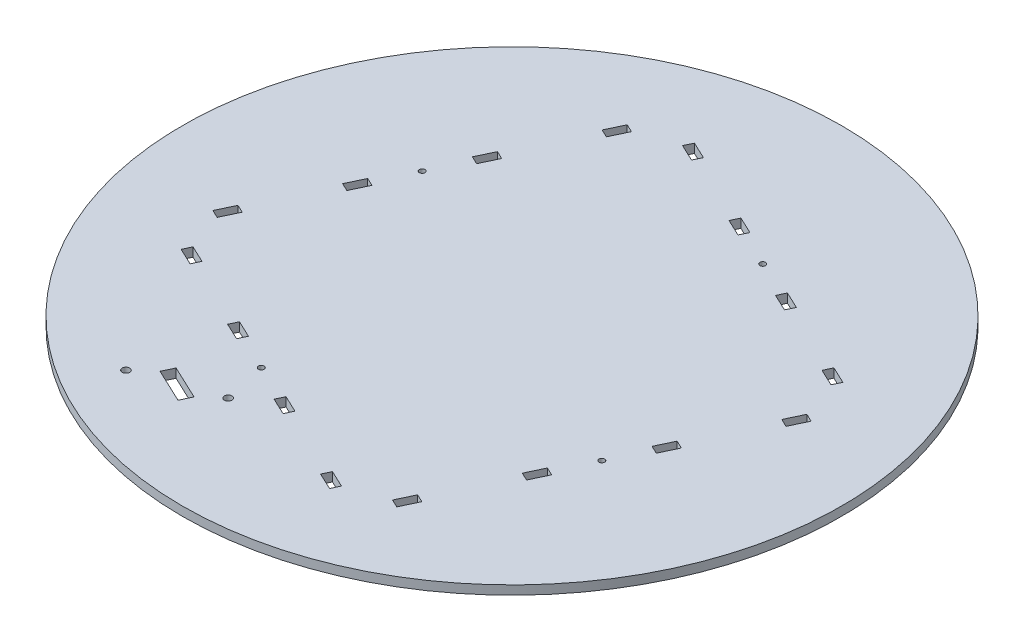
SolidWorks part; units mm, degrees
material "Oak"
ref_plane "Front Plane" through (0, 0, 0) normal (0, 0, 1) x (1, 0, 0)
ref_plane "Top Plane" through (0, 0, 0) normal (0, 1, 0) x (1, 0, 0)
ref_plane "Right Plane" through (0, 0, 0) normal (1, 0, 0) x (0, 0, -1)
sketch "Sketch1" plane through (0, 0, 0) normal (0, 1, 0) x (1, 0, 0)
  circle A0 centre (0, 0) radius 175
  dimension "D1" = 350
extrude "Boss-Extrude1" add sketch "Sketch1" along normal blind 4.75
sketch "Sketch2" plane through (0, 4.75, 0) normal (0, 1, 0) x (1, 0, 0)
  line L0 (33.006, -123.5643) -> (23.9642, -119.2927) construction
  line L1 (23.9642, -119.2927) -> (21.9352, -123.5875) construction
  line L2 (21.9352, -123.5875) -> (30.977, -127.8591) construction
  line L3 (30.977, -127.8591) -> (33.006, -123.5643) construction
  line L4 (-13.7851, -101.4587) -> (-22.8269, -97.1871) construction
  line L5 (-22.8269, -97.1871) -> (-24.8559, -101.482) construction
  line L6 (-24.8559, -101.482) -> (-15.8141, -105.7536) construction
  line L7 (-15.8141, -105.7536) -> (-13.7851, -101.4587) construction
  line L8 (-107.3673, -57.2476) -> (-116.4091, -52.976) construction
  line L9 (-116.4091, -52.976) -> (-118.4381, -57.2709) construction
  line L10 (-118.4381, -57.2709) -> (-109.3963, -61.5425) construction
  line L11 (-109.3963, -61.5425) -> (-107.3673, -57.2476) construction
  line L12 (-101.4587, 13.7851) -> (-97.1871, 22.8269) construction
  line L13 (-97.1871, 22.8269) -> (-101.482, 24.8559) construction
  line L14 (-101.482, 24.8559) -> (-105.7536, 15.8141) construction
  line L15 (-105.7536, 15.8141) -> (-101.4587, 13.7851) construction
  line L16 (-123.5643, -33.006) -> (-119.2927, -23.9642) construction
  line L17 (-119.2927, -23.9642) -> (-123.5875, -21.9352) construction
  line L18 (-123.5875, -21.9352) -> (-127.8591, -30.977) construction
  line L19 (-127.8591, -30.977) -> (-123.5643, -33.006) construction
  line L20 (33.006, -123.5643) -> (23.9642, -119.2927)
  line L21 (23.9642, -119.2927) -> (21.9352, -123.5875)
  line L22 (21.9352, -123.5875) -> (30.977, -127.8591)
  line L23 (30.977, -127.8591) -> (33.006, -123.5643)
  line L24 (-13.7851, -101.4587) -> (-22.8269, -97.1871)
  line L25 (-22.8269, -97.1871) -> (-24.8559, -101.482)
  line L26 (-24.8559, -101.482) -> (-15.8141, -105.7536)
  line L27 (-15.8141, -105.7536) -> (-13.7851, -101.4587)
  line L28 (-107.3673, -57.2476) -> (-116.4091, -52.976)
  line L29 (-116.4091, -52.976) -> (-118.4381, -57.2709)
  line L30 (-118.4381, -57.2709) -> (-109.3963, -61.5425)
  line L31 (-109.3963, -61.5425) -> (-107.3673, -57.2476)
  line L32 (-101.4587, 13.7851) -> (-97.1871, 22.8269)
  line L33 (-97.1871, 22.8269) -> (-101.482, 24.8559)
  line L34 (-101.482, 24.8559) -> (-105.7536, 15.8141)
  line L35 (-105.7536, 15.8141) -> (-101.4587, 13.7851)
  line L36 (-123.5643, -33.006) -> (-119.2927, -23.9642)
  line L37 (-119.2927, -23.9642) -> (-123.5875, -21.9352)
  line L38 (-123.5875, -21.9352) -> (-127.8591, -30.977)
  line L39 (-127.8591, -30.977) -> (-123.5643, -33.006)
  line L40 (107.3673, 57.2476) -> (116.4091, 52.976) construction
  line L41 (116.4091, 52.976) -> (118.4381, 57.2709) construction
  line L42 (118.4381, 57.2709) -> (109.3963, 61.5425) construction
  line L43 (109.3963, 61.5425) -> (107.3673, 57.2476) construction
  line L44 (-57.2476, 107.3673) -> (-52.976, 116.4091) construction
  line L45 (-52.976, 116.4091) -> (-57.2709, 118.4381) construction
  line L46 (-57.2709, 118.4381) -> (-61.5425, 109.3963) construction
  line L47 (-61.5425, 109.3963) -> (-57.2476, 107.3673) construction
  line L48 (60.5762, 79.3532) -> (69.618, 75.0816) construction
  line L49 (69.618, 75.0816) -> (71.647, 79.3764) construction
  line L50 (71.647, 79.3764) -> (62.6052, 83.648) construction
  line L51 (62.6052, 83.648) -> (60.5762, 79.3532) construction
  line L52 (13.7851, 101.4587) -> (22.8269, 97.1871) construction
  line L53 (22.8269, 97.1871) -> (24.8559, 101.482) construction
  line L54 (24.8559, 101.482) -> (15.8141, 105.7536) construction
  line L55 (15.8141, 105.7536) -> (13.7851, 101.4587) construction
  line L56 (-33.006, 123.5643) -> (-23.9642, 119.2927) construction
  line L57 (-23.9642, 119.2927) -> (-21.9352, 123.5875) construction
  line L58 (-21.9352, 123.5875) -> (-30.977, 127.8591) construction
  line L59 (-30.977, 127.8591) -> (-33.006, 123.5643) construction
  line L60 (-79.3532, 60.5762) -> (-75.0816, 69.618) construction
  line L61 (-75.0816, 69.618) -> (-79.3764, 71.647) construction
  line L62 (-79.3764, 71.647) -> (-83.648, 62.6052) construction
  line L63 (-83.648, 62.6052) -> (-79.3532, 60.5762) construction
  line L64 (-60.5762, -79.3532) -> (-69.618, -75.0816) construction
  line L65 (-69.618, -75.0816) -> (-71.647, -79.3764) construction
  line L66 (-71.647, -79.3764) -> (-62.6052, -83.648) construction
  line L67 (-62.6052, -83.648) -> (-60.5762, -79.3532) construction
  line L68 (123.5643, 33.006) -> (119.2927, 23.9642) construction
  line L69 (119.2927, 23.9642) -> (123.5875, 21.9352) construction
  line L70 (123.5875, 21.9352) -> (127.8591, 30.977) construction
  line L71 (127.8591, 30.977) -> (123.5643, 33.006) construction
  line L72 (101.4587, -13.7851) -> (97.1871, -22.8269) construction
  line L73 (97.1871, -22.8269) -> (101.482, -24.8559) construction
  line L74 (101.482, -24.8559) -> (105.7536, -15.8141) construction
  line L75 (105.7536, -15.8141) -> (101.4587, -13.7851) construction
  line L76 (79.3532, -60.5762) -> (75.0816, -69.618) construction
  line L77 (75.0816, -69.618) -> (79.3764, -71.647) construction
  line L78 (79.3764, -71.647) -> (83.648, -62.6052) construction
  line L79 (83.648, -62.6052) -> (79.3532, -60.5762) construction
  line L80 (57.2476, -107.3673) -> (52.976, -116.4091) construction
  line L81 (52.976, -116.4091) -> (57.2709, -118.4381) construction
  line L82 (57.2709, -118.4381) -> (61.5425, -109.3963) construction
  line L83 (61.5425, -109.3963) -> (57.2476, -107.3673) construction
  line L84 (107.3673, 57.2476) -> (116.4091, 52.976)
  line L85 (116.4091, 52.976) -> (118.4381, 57.2709)
  line L86 (118.4381, 57.2709) -> (109.3963, 61.5425)
  line L87 (109.3963, 61.5425) -> (107.3673, 57.2476)
  line L88 (-57.2476, 107.3673) -> (-52.976, 116.4091)
  line L89 (-52.976, 116.4091) -> (-57.2709, 118.4381)
  line L90 (-57.2709, 118.4381) -> (-61.5425, 109.3963)
  line L91 (-61.5425, 109.3963) -> (-57.2476, 107.3673)
  line L92 (60.5762, 79.3532) -> (69.618, 75.0816)
  line L93 (69.618, 75.0816) -> (71.647, 79.3764)
  line L94 (71.647, 79.3764) -> (62.6052, 83.648)
  line L95 (62.6052, 83.648) -> (60.5762, 79.3532)
  line L96 (13.7851, 101.4587) -> (22.8269, 97.1871)
  line L97 (22.8269, 97.1871) -> (24.8559, 101.482)
  line L98 (24.8559, 101.482) -> (15.8141, 105.7536)
  line L99 (15.8141, 105.7536) -> (13.7851, 101.4587)
  line L100 (-33.006, 123.5643) -> (-23.9642, 119.2927)
  line L101 (-23.9642, 119.2927) -> (-21.9352, 123.5875)
  line L102 (-21.9352, 123.5875) -> (-30.977, 127.8591)
  line L103 (-30.977, 127.8591) -> (-33.006, 123.5643)
  line L104 (-79.3532, 60.5762) -> (-75.0816, 69.618)
  line L105 (-75.0816, 69.618) -> (-79.3764, 71.647)
  line L106 (-79.3764, 71.647) -> (-83.648, 62.6052)
  line L107 (-83.648, 62.6052) -> (-79.3532, 60.5762)
  line L108 (-60.5762, -79.3532) -> (-69.618, -75.0816)
  line L109 (-69.618, -75.0816) -> (-71.647, -79.3764)
  line L110 (-71.647, -79.3764) -> (-62.6052, -83.648)
  line L111 (-62.6052, -83.648) -> (-60.5762, -79.3532)
  line L112 (123.5643, 33.006) -> (119.2927, 23.9642)
  line L113 (119.2927, 23.9642) -> (123.5875, 21.9352)
  line L114 (123.5875, 21.9352) -> (127.8591, 30.977)
  line L115 (127.8591, 30.977) -> (123.5643, 33.006)
  line L116 (101.4587, -13.7851) -> (97.1871, -22.8269)
  line L117 (97.1871, -22.8269) -> (101.482, -24.8559)
  line L118 (101.482, -24.8559) -> (105.7536, -15.8141)
  line L119 (105.7536, -15.8141) -> (101.4587, -13.7851)
  line L120 (79.3532, -60.5762) -> (75.0816, -69.618)
  line L121 (75.0816, -69.618) -> (79.3764, -71.647)
  line L122 (79.3764, -71.647) -> (83.648, -62.6052)
  line L123 (83.648, -62.6052) -> (79.3532, -60.5762)
  line L124 (57.2476, -107.3673) -> (52.976, -116.4091)
  line L125 (52.976, -116.4091) -> (57.2709, -118.4381)
  line L126 (57.2709, -118.4381) -> (61.5425, -109.3963)
  line L127 (61.5425, -109.3963) -> (57.2476, -107.3673)
extrude "Cut-Extrude1" cut sketch "Sketch2" against normal blind 4.75
sketch "Sketch3" plane through (0, 4.75, 0) normal (0, 1, 0) x (1, 0, 0)
  line L0 (12.4764, 52.4112) -> (39.3092, 38.9948)
  line L1 (12.4764, 52.4112) -> (41.5453, 110.549)
  line L2 (39.3092, 38.9948) -> (68.3781, 97.1326)
  line L3 (41.5453, 110.549) -> (68.3781, 97.1326)
  line L4 (23.6567, 97.1326) -> (68.3781, 130.6736)
  line L5 (68.3781, 130.6736) -> (68.3781, 74.7719)
  line L6 (68.3781, 74.7719) -> (23.6567, 97.1326)
  point P8 (25.8928, 45.703)
  dimension "D1" = 30
  dimension "D2" = 45
  dimension "D3" = 65
  dimension "D4" = 50
sketch "Sketch4" plane through (0, 4.75, 0) normal (0, 1, 0) x (1, 0, 0)
  line L0 (-47.129, -121.7057) -> (-65.2125, -113.1625) construction
  line L1 (-65.2125, -113.1625) -> (-67.9463, -118.9492) construction
  line L2 (-49.8628, -127.4924) -> (-47.129, -121.7057) construction
  line L3 (-67.9463, -118.9492) -> (-49.8628, -127.4924) construction
  line L4 (-47.129, -121.7057) -> (-65.2125, -113.1625)
  line L5 (-65.2125, -113.1625) -> (-67.9463, -118.9492)
  line L6 (-49.8628, -127.4924) -> (-47.129, -121.7057)
  line L7 (-67.9463, -118.9492) -> (-49.8628, -127.4924)
  circle A0 centre (-77.5077, -127.4827) radius 2 construction
  circle A1 centre (-37.5676, -113.1722) radius 2 construction
  circle A2 centre (-77.5077, -127.4827) radius 2
  circle A3 centre (-37.5676, -113.1722) radius 2
extrude "Cut-Extrude2" cut sketch "Sketch4" against normal through all
sketch "Sketch5" plane through (0, 4.75, 0) normal (0, 1, 0) x (1, 0, 0)
  line L0 (44.0723, 89.7768) -> (41.3598, 91.0583) construction
  line L1 (43.0578, 87.6294) -> (45.0868, 91.9243) construction
  line L4 (40.3453, 88.9109) -> (42.3743, 93.2057) construction
  line L5 (40.3453, 88.9109) -> (42.3743, 93.2057) construction
  line L6 (43.0578, 87.6294) -> (45.0868, 91.9243) construction
  circle A0 centre (42.7161, 90.4176) radius 1.5
  circle A1 centre (90.4176, -42.7161) radius 1.5
  circle A2 centre (-42.7161, -90.4176) radius 1.5
  circle A3 centre (-90.4176, 42.7161) radius 1.5
  point P4 (42.7161, 90.4176)
  dimension "D1" = 3
  dimension "D2" = 4
extrude "Cut-Extrude3" cut sketch "Sketch5" against normal through all
